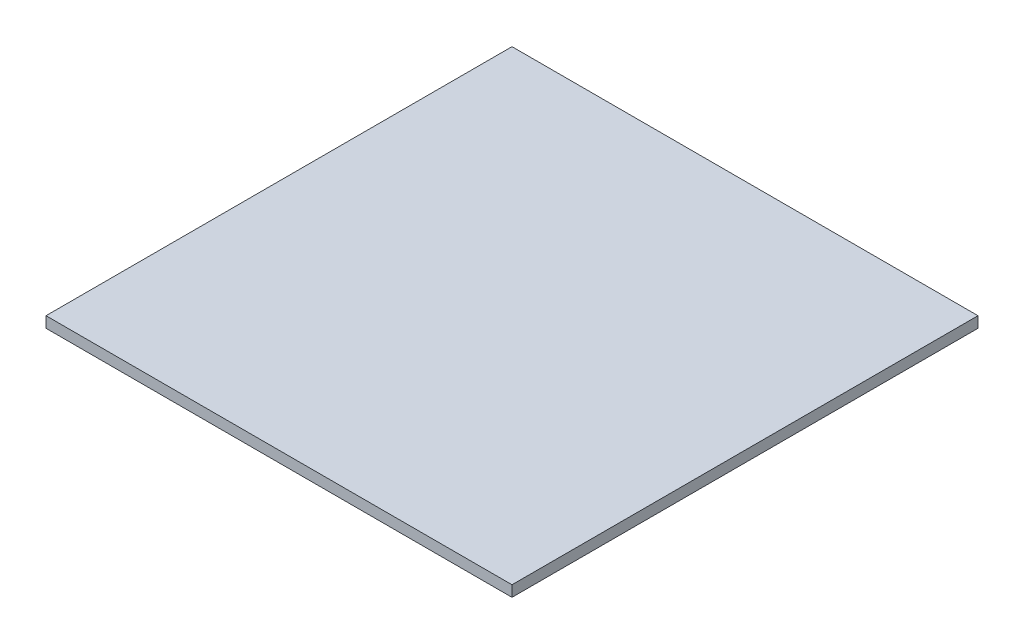
SolidWorks part; units mm, degrees
material "Teak"
ref_plane "Front Plane" through (0, 0, 0) normal (0, 0, 1) x (1, 0, 0)
ref_plane "Top Plane" through (0, 0, 0) normal (0, 1, 0) x (1, 0, 0)
ref_plane "Right Plane" through (0, 0, 0) normal (1, 0, 0) x (0, 0, -1)
sketch "Sketch1" plane through (0, 0, 0) normal (0, 1, 0) x (1, 0, 0)
  line L1 (0, 0) -> (812.8, 0)
  line L2 (0, 0) -> (0, 812.8)
  line L3 (0, 812.8) -> (812.8, 812.8)
  line L4 (812.8, 0) -> (812.8, 812.8)
  dimension "D1" = 812.8
  dimension "D2" = 812.8
extrude "Boss-Extrude1" add sketch "Sketch1" along normal blind 19.05
